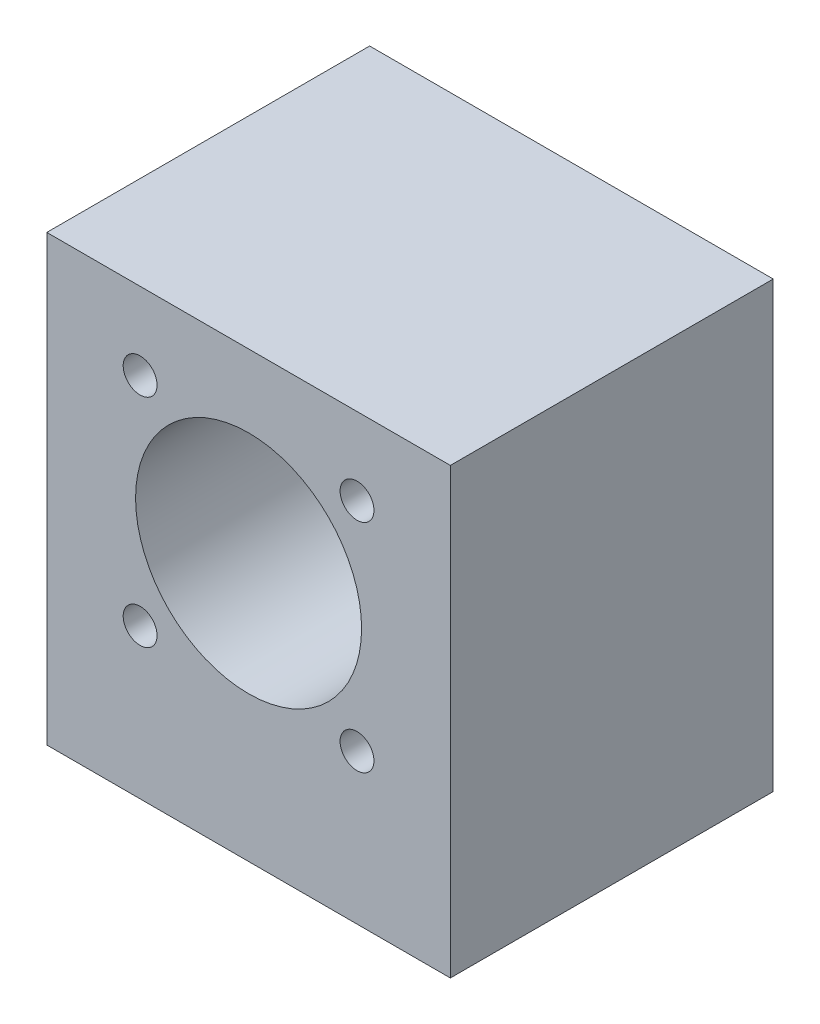
SolidWorks part; units mm, degrees
ref_plane "Front Plane" through (0, 0, 0) normal (0, 0, 1) x (1, 0, 0)
ref_plane "Top Plane" through (0, 0, 0) normal (0, 1, 0) x (1, 0, 0)
ref_plane "Right Plane" through (0, 0, 0) normal (1, 0, 0) x (0, 0, -1)
sketch "Sketch1" plane through (0, 0, 0) normal (0, 0, 1) x (1, 0, 0)
  line L1 (25, -27.5) -> (-25, -27.5)
  line L2 (25, -27.5) -> (25, 27.5)
  line L3 (25, 27.5) -> (-25, 27.5)
  line L4 (-25, -27.5) -> (-25, 27.5)
  line L5 (25, -27.5) -> (-25, 27.5) construction
  line L6 (25, 27.5) -> (-25, -27.5) construction
  point P0 (0, 0)
  dimension "D1" = 50
  dimension "D2" = 55
extrude "Boss-Extrude1" add sketch "Sketch1" against normal blind 40
sketch "Sketch2" plane through (0, 0, 0) normal (0, 0, 1) x (1, 0, 0)
  line L0 (0, 27.5) -> (0, -27.5) construction
  line L1 (25, 27.5) -> (-25, 27.5) construction
  line L2 (-25, -27.5) -> (25, -27.5) construction
  line L3 (-25, 4.5) -> (25, 4.5) construction
  line L4 (-25, 27.5) -> (-25, -27.5) construction
  line L5 (25, -27.5) -> (25, 27.5) construction
  circle A0 centre (0, 4.5) radius 14
  dimension "D1" = 28
  dimension "D2" = 23
extrude "Cut-Extrude1" cut sketch "Sketch2" against normal through all
sketch "Sketch3" plane through (0, 0, 0) normal (0, 0, 1) x (1, 0, 0)
  line L0 (0, 4.5) -> (13.435, 17.935) construction
  line L1 (0, 4.5) -> (19, 4.5) construction
  line L3 (0, 4.5) -> (0, -14.5) construction
  circle A0 centre (0, 4.5) radius 19 construction
  point P3 (-13.435, 17.935)
  point P7 (13.435, -8.935)
  point P8 (-13.435, -8.935)
  dimension "D1" = 38
  dimension "D2" = 45
sketch "Sketch4" plane through (0, -27.5, 0) normal (0, -1, 0) x (1, 0, 0)
  line L0 (0, 0) -> (0, -40) construction
  line L1 (19, 0) -> (-19, 0) construction
  line L2 (-25, -40) -> (25, -40) construction
  line L3 (-25, -20) -> (25, -20) construction
  line L4 (-25, -40) -> (-25, 0) construction
  line L5 (25, -40) -> (25, 0) construction
  point P12 (-20, -8)
  point P13 (20, -8)
  point P14 (20, -32)
  point P15 (-20, -32)
  dimension "D1" = 12
  dimension "D2" = 20
hole_wizard "M5 Tapped Hole1" positions "3DSketch1" profile "Sketch6" tap size "M5" standard "ISO"
sketch3d "3DSketch1"
  point P0 (-20, -27.5, -8)
  point P3 (20, -27.5, -8)
  point P6 (20, -27.5, -32)
  point P9 (-20, -27.5, -32)
sketch "Sketch6" plane through (-20, -27.5, -8) normal (1, 0, 0) x (0, 0, -1)
  line L0 (0, 0) -> (0, 16.2618)
  line L1 (0, 16.2618) -> (2.1, 15)
  line L2 (2.1, 15) -> (2.1, 0)
  line L5 (2.1, 0) -> (0, 0)
  line L10 (0, 16.2618) -> (-2.1, 15) construction
  line L11 (0, -6.35) -> (0, 107.95) construction
  dimension "Tap Drill Dia." = 4.2
  dimension "Tap Drill Depth" = 15
  dimension "Drill Angle" = 118
cosmetic thread "Hole Thread1" parameters "D1"=14.5, "D2"=5
cosmetic thread "Hole Thread2" parameters "D1"=14.5, "D2"=5
cosmetic thread "Hole Thread3" parameters "D1"=14.5, "D2"=5
cosmetic thread "Hole Thread4" parameters "D1"=14.5, "D2"=5
hole_wizard "M5 Tapped Hole3" positions "3DSketch3" profile "Sketch8" tap size "M5" standard "ISO"
sketch3d "3DSketch3"
  point P0 (13.435, 17.935, 0)
  point P3 (13.435, -8.935, 0)
  point P6 (-13.435, -8.935, 0)
  point P9 (-13.435, 17.935, 0)
sketch "Sketch8" plane through (13.435, 17.935, 0) normal (1, 0, 0) x (0, -1, 0)
  line L0 (0, 0) -> (0, 18.6618)
  line L1 (0, 18.6618) -> (2.1, 17.4)
  line L2 (2.1, 17.4) -> (2.1, 0)
  line L5 (2.1, 0) -> (0, 0)
  line L10 (0, 18.6618) -> (-2.1, 17.4) construction
  line L11 (0, -6.35) -> (0, 107.95) construction
  dimension "Tap Drill Dia." = 4.2
  dimension "Tap Drill Depth" = 17.4
  dimension "Drill Angle" = 118
